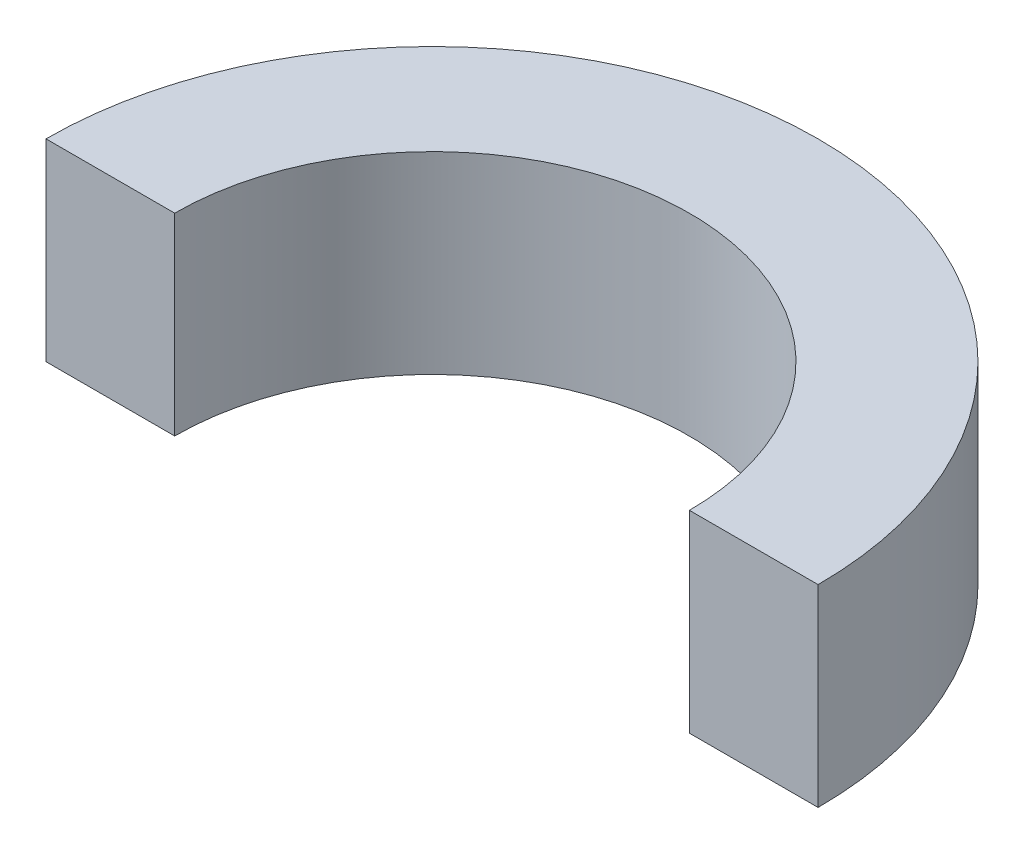
SolidWorks part; units mm, degrees
ref_plane "Front Plane" through (0, 0, 0) normal (0, 0, 1) x (1, 0, 0)
ref_plane "Top Plane" through (0, 0, 0) normal (0, 1, 0) x (1, 0, 0)
ref_plane "Right Plane" through (0, 0, 0) normal (1, 0, 0) x (0, 0, -1)
sketch "Sketch1" plane through (0, 0, 0) normal (0, 1, 0) x (1, 0, 0)
  line L1 (-30, 0) -> (-20, 0)
  line L2 (20, 0) -> (30, 0)
  arc A0 (-30, 0) -> (30, 0) centre (0, 0) cw
  arc A1 (-20, 0) -> (20, 0) centre (0, 0) cw
  point P6 (0, 0)
  dimension "D1" = 20
  dimension "D2" = 30
extrude "Boss-Extrude1" add sketch "Sketch1" along normal blind 15
